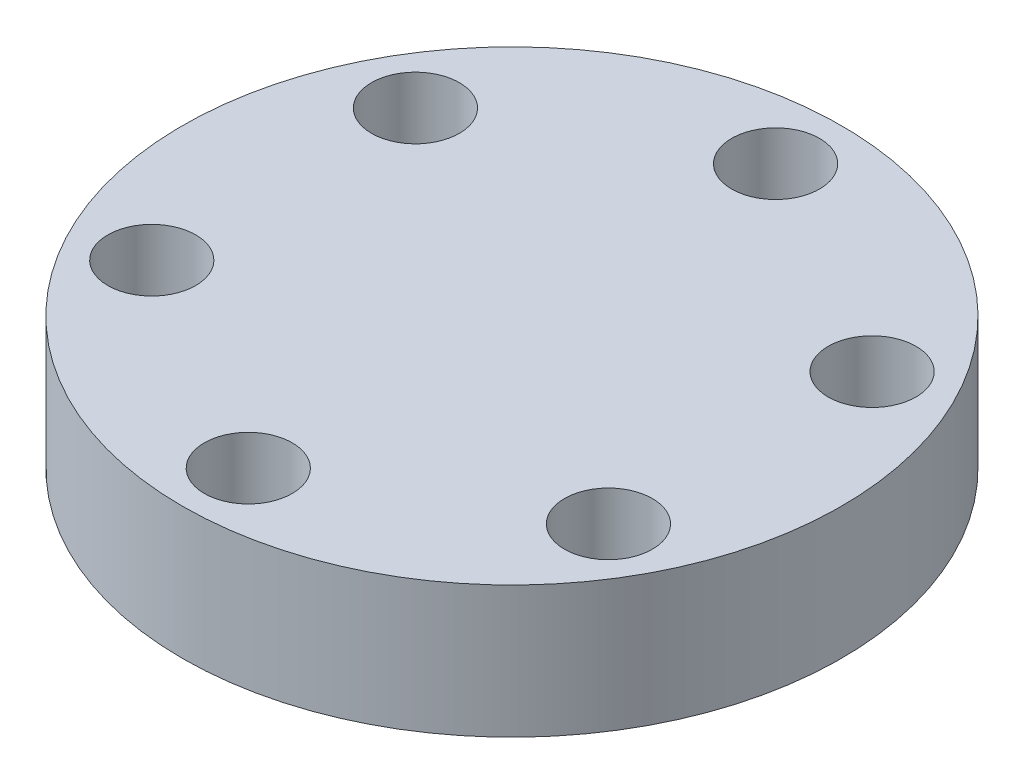
SolidWorks part; units mm, degrees
material "1060 Alloy"
ref_plane "Front Plane" through (0, 0, 0) normal (0, 0, 1) x (1, 0, 0)
ref_plane "Top Plane" through (0, 0, 0) normal (0, 1, 0) x (1, 0, 0)
ref_plane "Right Plane" through (0, 0, 0) normal (1, 0, 0) x (0, 0, -1)
sketch "Sketch1" plane through (0, 0, 0) normal (0, 1, 0) x (1, 0, 0)
  circle A0 centre (0, 0) radius 15
extrude "Boss-Extrude1" add sketch "Sketch1" along normal blind 30
sketch "Sketch2" plane through (0, 0, 0) normal (0, -1, 0) x (1, 0, 0)
  circle A0 centre (0, 0) radius 7
extrude "Boss-Extrude2" add sketch "Sketch2" along normal blind 4
hole_wizard "Ø4.0mm Dowel Hole1" positions "Sketch3" profile "Sketch5" hole size "Ø4.0" standard "ISO" end condition through all
sketch "Sketch3" plane through (0, 0, 0) normal (0, -1, 0) x (-1, 0, 0)
  line L0 (0, 44.7868) -> (0, -44.7868) construction
  point P0 (0, -12)
  dimension "D1" = 12
sketch "Sketch5" plane through (0, 0, 12) normal (1, 0, 0) x (0, 0, -1)
  line L0 (0, 0) -> (0, 30)
  line L1 (0, 30) -> (2, 30)
  line L2 (2, 30) -> (2, 0)
  line L5 (2, 0) -> (0, 0)
  line L11 (0, -6.35) -> (0, 107.95) construction
  dimension "Thru Hole Dia." = 4
  dimension "Thru Hole Depth" = 30
pattern_circular "CirPattern1" count 6 over 360 about axis through (0, 0, 0) along (0, 1, 0) of "Ø4.0mm Dowel Hole1"
sketch "Sketch6" plane through (0, 30, 0) normal (0, 1, 0) x (1, 0, 0)
  circle A0 centre (-10.3923, 6) radius 2 construction
  circle A1 centre (0, 0) radius 15
  circle A2 centre (0, 0) radius 15
  circle A3 centre (-10.3923, -6) radius 2 construction
  circle A4 centre (0, -12) radius 2 construction
  circle A5 centre (10.3923, -6) radius 2 construction
  circle A6 centre (10.3923, 6) radius 2 construction
  circle A7 centre (0, 12) radius 2 construction
  circle A8 centre (-10.3923, 6) radius 2
  circle A9 centre (-10.3923, -6) radius 2
  circle A10 centre (0, -12) radius 2
  circle A11 centre (10.3923, -6) radius 2
  circle A12 centre (10.3923, 6) radius 2
  circle A13 centre (0, 12) radius 2
  dimension "D1" = 0
extrude "Boss-Extrude3" add sketch "Sketch6" along normal blind 6 separate body
delete or keep bodies "Body-Delete/Keep 1" bodies 111
